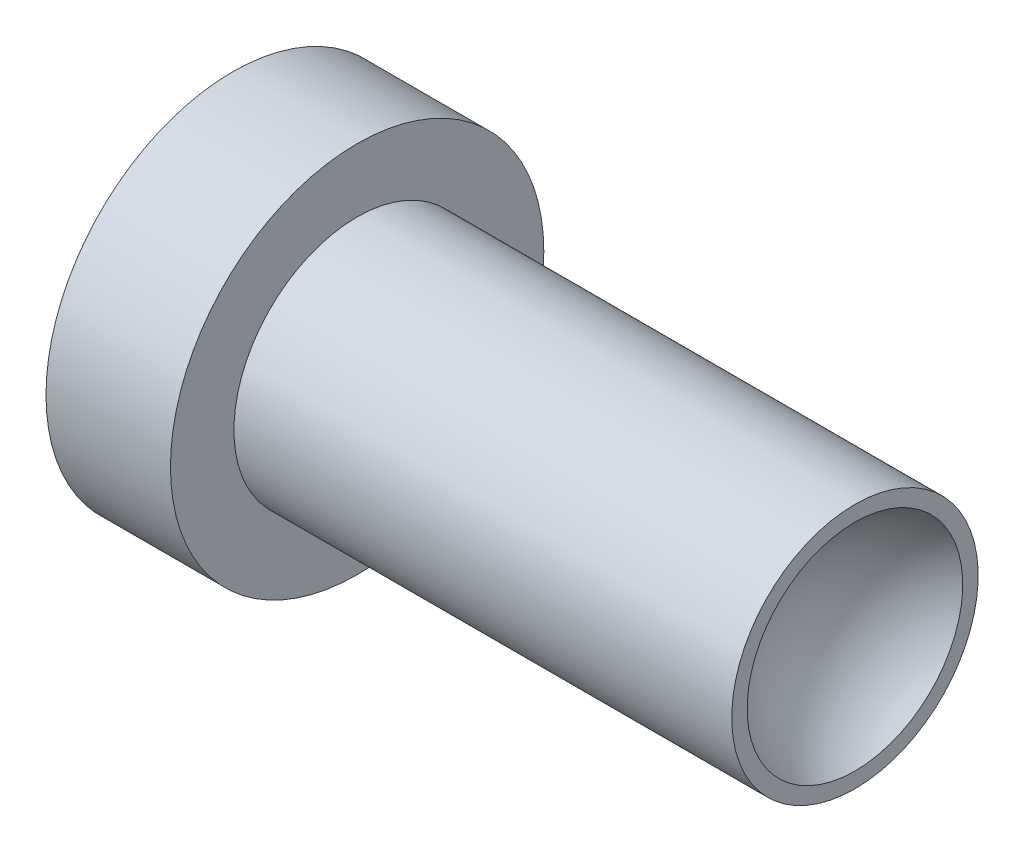
SolidWorks part; units mm, degrees
ref_plane "Front Plane" through (0, 0, 0) normal (0, 0, 1) x (1, 0, 0)
ref_plane "Top Plane" through (0, 0, 0) normal (0, 1, 0) x (1, 0, 0)
ref_plane "Right Plane" through (0, 0, 0) normal (1, 0, 0) x (0, 0, -1)
sketch "Sketch1" plane through (0, 0, 0) normal (0, 0, 1) x (1, 0, 0)
  line L0 (0, 0) -> (0, 19.05)
  line L1 (0, 19.05) -> (12.7, 19.05)
  line L2 (12.7, 19.05) -> (12.7, 12.573)
  line L3 (12.7, 12.573) -> (63.5, 12.573)
  line L4 (63.5, 12.573) -> (63.5, 0)
  line L5 (63.5, 0) -> (0, 0)
  dimension "D1" = 19.05
  dimension "D2" = 12.573
  dimension "D3" = 12.7
  dimension "D4" = 50.8
revolve "Revolve1" add sketch "Sketch1" angle 360 about L5
sketch "Sketch2" plane through (0, 0, 0) normal (0, 0, 1) x (1, 0, 0)
  line L0 (63.5, -12.573) -> (63.5, 12.573) construction
  line L1 (57.15, 0) -> (63.5, 0)
  line L2 (63.5, 0) -> (63.5, 10.9985)
  arc A0 (63.5, 10.9985) -> (57.15, 0) centre (69.85, 0) ccw
  dimension "D2" = 12.7
  dimension "D1" = 6.35
revolve "Cut-Revolve1" cut sketch "Sketch2" angle 360 about L1
